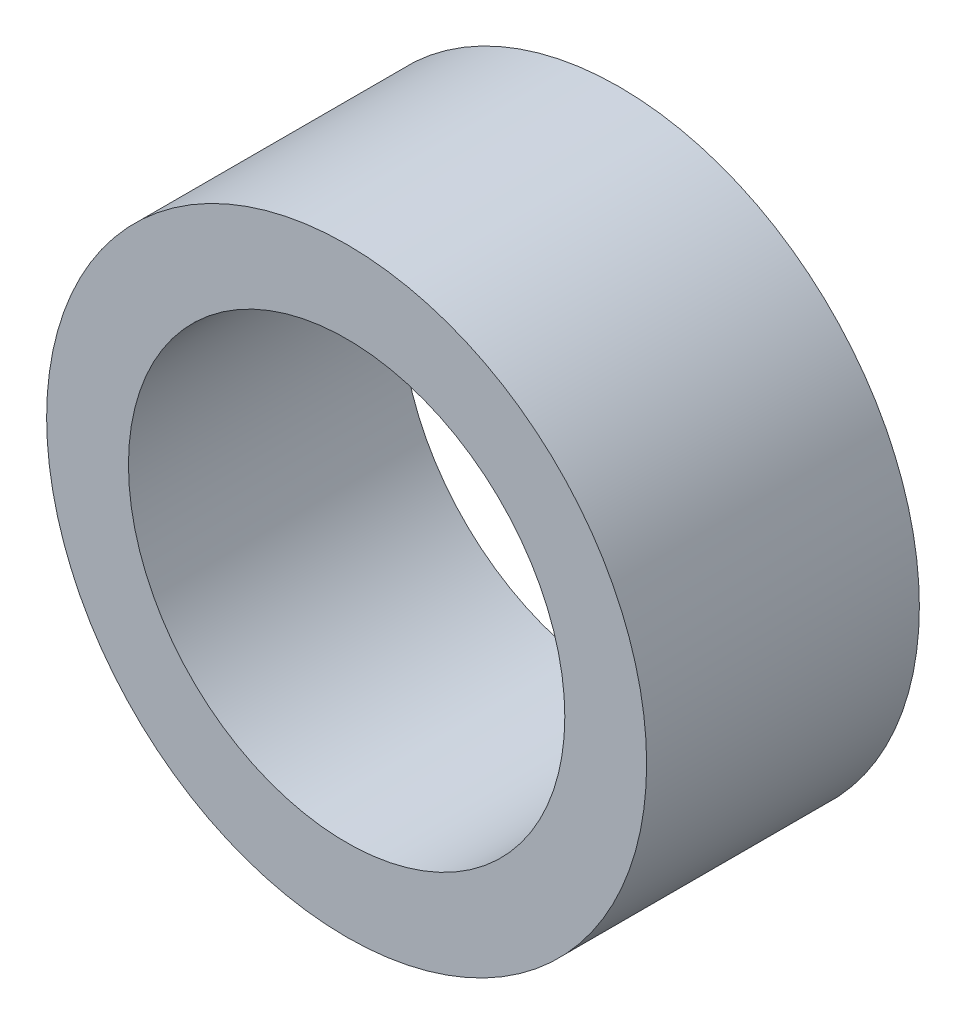
SolidWorks part; units mm, degrees
ref_plane "Front Plane" through (0, 0, 0) normal (0, 0, 1) x (1, 0, 0)
ref_plane "Top Plane" through (0, 0, 0) normal (0, 1, 0) x (1, 0, 0)
ref_plane "Right Plane" through (0, 0, 0) normal (1, 0, 0) x (0, 0, -1)
sketch "Sketch1" plane through (0, 0, 0) normal (0, 0, 1) x (1, 0, 0)
  circle A0 centre (0, 0) radius 8
  circle A1 centre (0, 0) radius 11
  dimension "D1" = 16
  dimension "D2" = 22
extrude "Boss-Extrude1" add sketch "Sketch1" along normal mid plane 10
